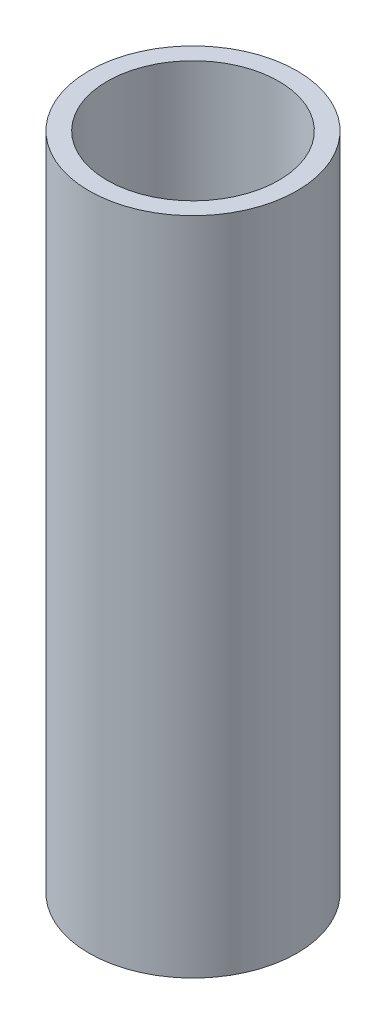
SolidWorks part; units mm, degrees
ref_plane "정면" through (0, 0, 0) normal (0, 0, 1) x (1, 0, 0)
ref_plane "윗면" through (0, 0, 0) normal (0, 1, 0) x (1, 0, 0)
ref_plane "우측면" through (0, 0, 0) normal (1, 0, 0) x (0, 0, -1)
sketch "스케치1" plane through (0, 0, 0) normal (0, 1, 0) x (1, 0, 0)
  circle A0 centre (0, 0) radius 12.6
  dimension "D1" = 25.2
extrude "보스-돌출1" add sketch "스케치1" along normal blind 80
shell "쉘1" thickness 2.2
